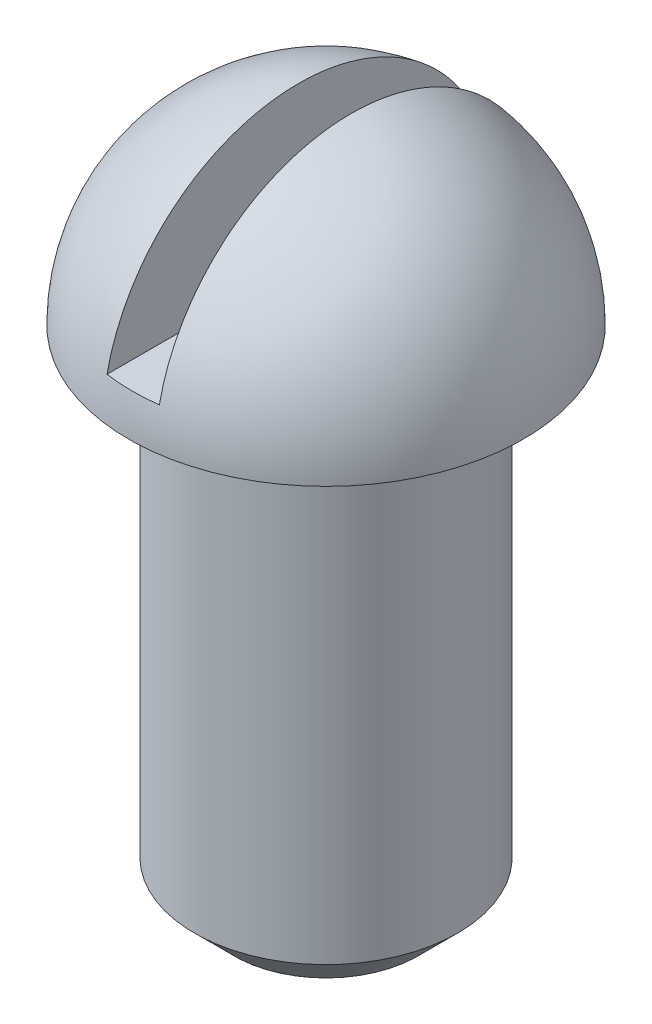
SolidWorks part; units mm, degrees
ref_plane "Front Plane" through (0, 0, 0) normal (0, 0, 1) x (1, 0, 0)
ref_plane "Top Plane" through (0, 0, 0) normal (0, 1, 0) x (1, 0, 0)
ref_plane "Right Plane" through (0, 0, 0) normal (1, 0, 0) x (0, 0, -1)
sketch "Sketch1" plane through (0, 0, 0) normal (0, 0, 1) x (1, 0, 0)
  line L0 (0, 0) -> (0, 38)
  line L2 (-10, 38) -> (-10, 3)
  line L3 (-7, 0) -> (0, 0)
  line L4 (-10, 3) -> (-7, 0)
  line L5 (-10, 38) -> (-15, 38)
  line L7 (0, 38) -> (0, 53)
  arc A0 (-15, 38) -> (0, 53) centre (0, 38) cw
  point P5 (-10, 0)
  dimension "D6" = 35
  dimension "D8" = 15
  dimension "D1" = 10
  dimension "D2" = 38
  dimension "D3" = 3
  dimension "D4" = 45
  dimension "D5" = 5
  dimension "D7" = 15
revolve "Revolve1" add sketch "Sketch1" angle 360 about L0
sketch "Sketch2" plane through (0, 0, 0) normal (0, 0, 1) x (1, 0, 0)
  line L0 (0, 0) -> (0, 37.9991) construction
  line L1 (0.1655, 40.9991) -> (15.2272, 40.9991) construction
  line L2 (0, 37.9991) -> (0, 54.095) construction
  line L3 (0, 37.9991) -> (50000, 37.9991) construction
  line L4 (1.9116, 40.9991) -> (1.9116, 54.4879)
  line L5 (1.9116, 54.4879) -> (-2.0884, 54.4879)
  line L6 (-2.0884, 54.4879) -> (-2.0884, 40.9991)
  line L7 (-2.0884, 40.9991) -> (1.9116, 40.9991)
  dimension "D1" = 3
  dimension "D2" = 4
  dimension "D3" = 13.4888
extrude "Cut-Extrude1" cut sketch "Sketch2" against normal through all both and the other way through all
